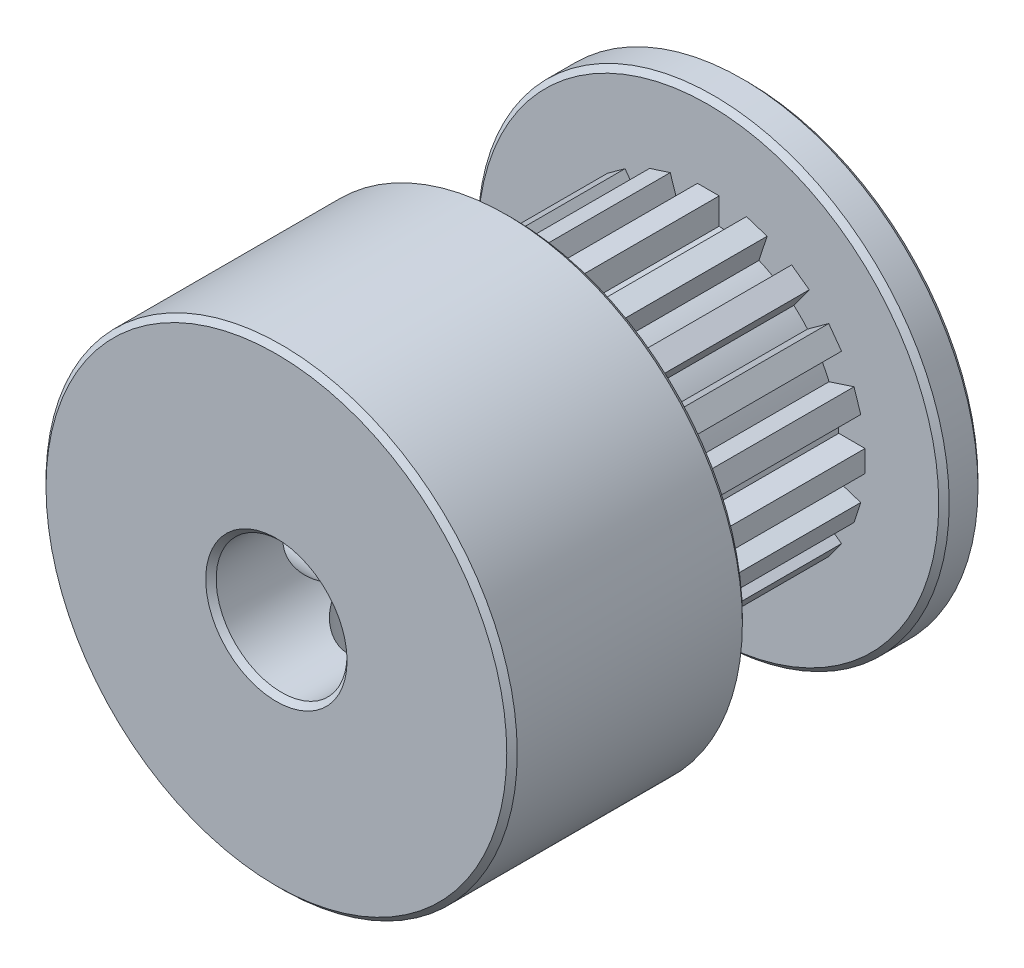
SolidWorks part; units mm, degrees
ref_plane "前视基准面" through (0, 0, 0) normal (0, 0, 1) x (1, 0, 0)
ref_plane "上视基准面" through (0, 0, 0) normal (0, 1, 0) x (1, 0, 0)
ref_plane "右视基准面" through (0, 0, 0) normal (1, 0, 0) x (0, 0, -1)
sketch "草图1" plane through (0, 0, 0) normal (0, 0, 1) x (1, 0, 0)
  circle A0 centre (0, 0) radius 2.5
  circle A1 centre (0, 0) radius 9
  dimension "D1" = 5
  dimension "D2" = 18
extrude "凸台-拉伸1" add sketch "草图1" along normal blind 1.5
sketch "草图2" plane through (0, 0, 1.5) normal (0, 0, 1) x (1, 0, 0)
  line L0 (0, 6) -> (0, 0) construction
  line L1 (-0.415, 5.9856) -> (-0.415, 4.9827)
  line L2 (-0.415, 5.9856) -> (0.415, 5.9856)
  line L3 (0.415, 5.9856) -> (0.415, 4.9827)
  line L4 (1.455, 5.8209) -> (1.1451, 4.8671)
  line L5 (2.2444, 5.5644) -> (1.9344, 4.6106)
  line L6 (1.455, 5.8209) -> (2.2444, 5.5644)
  line L7 (3.1825, 5.0864) -> (2.593, 4.2751)
  line L8 (3.854, 4.5985) -> (3.2645, 3.7872)
  line L9 (3.1825, 5.0864) -> (3.854, 4.5985)
  line L10 (4.5985, 3.854) -> (3.7872, 3.2645)
  line L11 (5.0864, 3.1825) -> (4.2751, 2.593)
  line L12 (4.5985, 3.854) -> (5.0864, 3.1825)
  line L13 (5.5644, 2.2444) -> (4.6106, 1.9344)
  line L14 (5.8209, 1.455) -> (4.8671, 1.1451)
  line L15 (5.5644, 2.2444) -> (5.8209, 1.455)
  line L16 (5.9856, 0.415) -> (4.9827, 0.415)
  line L17 (5.9856, -0.415) -> (4.9827, -0.415)
  line L18 (5.9856, 0.415) -> (5.9856, -0.415)
  line L19 (5.8209, -1.455) -> (4.8671, -1.1451)
  line L20 (5.5644, -2.2444) -> (4.6106, -1.9344)
  line L21 (5.8209, -1.455) -> (5.5644, -2.2444)
  line L22 (5.0864, -3.1825) -> (4.2751, -2.593)
  line L23 (4.5985, -3.854) -> (3.7872, -3.2645)
  line L24 (5.0864, -3.1825) -> (4.5985, -3.854)
  line L25 (3.854, -4.5985) -> (3.2645, -3.7872)
  line L26 (3.1825, -5.0864) -> (2.593, -4.2751)
  line L27 (3.854, -4.5985) -> (3.1825, -5.0864)
  line L28 (2.2444, -5.5644) -> (1.9344, -4.6106)
  line L29 (1.455, -5.8209) -> (1.1451, -4.8671)
  line L30 (2.2444, -5.5644) -> (1.455, -5.8209)
  line L31 (0.415, -5.9856) -> (0.415, -4.9827)
  line L32 (-0.415, -5.9856) -> (-0.415, -4.9827)
  line L33 (0.415, -5.9856) -> (-0.415, -5.9856)
  line L34 (-1.455, -5.8209) -> (-1.1451, -4.8671)
  line L35 (-2.2444, -5.5644) -> (-1.9344, -4.6106)
  line L36 (-1.455, -5.8209) -> (-2.2444, -5.5644)
  line L37 (-3.1825, -5.0864) -> (-2.593, -4.2751)
  line L38 (-3.854, -4.5985) -> (-3.2645, -3.7872)
  line L39 (-3.1825, -5.0864) -> (-3.854, -4.5985)
  line L40 (-4.5985, -3.854) -> (-3.7872, -3.2645)
  line L41 (-5.0864, -3.1825) -> (-4.2751, -2.593)
  line L42 (-4.5985, -3.854) -> (-5.0864, -3.1825)
  line L43 (-5.5644, -2.2444) -> (-4.6106, -1.9344)
  line L44 (-5.8209, -1.455) -> (-4.8671, -1.1451)
  line L45 (-5.5644, -2.2444) -> (-5.8209, -1.455)
  line L46 (-5.9856, -0.415) -> (-4.9827, -0.415)
  line L47 (-5.9856, 0.415) -> (-4.9827, 0.415)
  line L48 (-5.9856, -0.415) -> (-5.9856, 0.415)
  line L49 (-5.8209, 1.455) -> (-4.8671, 1.1451)
  line L50 (-5.5644, 2.2444) -> (-4.6106, 1.9344)
  line L51 (-5.8209, 1.455) -> (-5.5644, 2.2444)
  line L52 (-5.0864, 3.1825) -> (-4.2751, 2.593)
  line L53 (-4.5985, 3.854) -> (-3.7872, 3.2645)
  line L54 (-5.0864, 3.1825) -> (-4.5985, 3.854)
  line L55 (-3.854, 4.5985) -> (-3.2645, 3.7872)
  line L56 (-3.1825, 5.0864) -> (-2.593, 4.2751)
  line L57 (-3.854, 4.5985) -> (-3.1825, 5.0864)
  line L58 (-2.2444, 5.5644) -> (-1.9344, 4.6106)
  line L59 (-1.455, 5.8209) -> (-1.1451, 4.8671)
  line L60 (-2.2444, 5.5644) -> (-1.455, 5.8209)
  circle A0 centre (0, 0) radius 6 construction
  circle A1 centre (0, 0) radius 2.5 construction
  circle A2 centre (0, 0) radius 2.5
  arc A3 (-1.9344, 4.6106) -> (-2.593, 4.2751) centre (0, 0) ccw
  arc A4 (-0.415, 4.9827) -> (-1.1451, 4.8671) centre (0, 0) ccw
  arc A5 (1.1451, 4.8671) -> (0.415, 4.9827) centre (0, 0) ccw
  arc A6 (2.593, 4.2751) -> (1.9344, 4.6106) centre (0, 0) ccw
  arc A7 (3.7872, 3.2645) -> (3.2645, 3.7872) centre (0, 0) ccw
  arc A8 (4.6106, 1.9344) -> (4.2751, 2.593) centre (0, 0) ccw
  arc A9 (4.9827, 0.415) -> (4.8671, 1.1451) centre (0, 0) ccw
  arc A10 (4.8671, -1.1451) -> (4.9827, -0.415) centre (0, 0) ccw
  arc A11 (4.2751, -2.593) -> (4.6106, -1.9344) centre (0, 0) ccw
  arc A12 (3.2645, -3.7872) -> (3.7872, -3.2645) centre (0, 0) ccw
  arc A13 (0.415, -4.9827) -> (1.1451, -4.8671) centre (0, 0) ccw
  arc A14 (-2.593, -4.2751) -> (-1.9344, -4.6106) centre (0, 0) ccw
  arc A15 (-3.7872, -3.2645) -> (-3.2645, -3.7872) centre (0, 0) ccw
  arc A16 (-1.1451, -4.8671) -> (-0.415, -4.9827) centre (0, 0) ccw
  arc A17 (1.9344, -4.6106) -> (2.593, -4.2751) centre (0, 0) ccw
  arc A18 (-4.6106, -1.9344) -> (-4.2751, -2.593) centre (0, 0) ccw
  arc A19 (-4.9827, -0.415) -> (-4.8671, -1.1451) centre (0, 0) ccw
  arc A20 (-4.8671, 1.1451) -> (-4.9827, 0.415) centre (0, 0) ccw
  arc A21 (-4.2751, 2.593) -> (-4.6106, 1.9344) centre (0, 0) ccw
  arc A22 (-3.2645, 3.7872) -> (-3.7872, 3.2645) centre (0, 0) ccw
  point P89 (0, 0)
  dimension "D1" = 12
  dimension "D2" = 10
  dimension "D3" = 0.83
  dimension "D4" = 20
extrude "凸台-拉伸2" add sketch "草图2" along normal blind 7.5
sketch "草图3" plane through (0, 0, 9) normal (0, 0, 1) x (1, 0, 0)
  circle A0 centre (0, 0) radius 2.5 construction
  circle A1 centre (0, 0) radius 9
  circle A2 centre (0, 0) radius 9
  circle A3 centre (0, 0) radius 2.5
  dimension "D1" = 0
extrude "凸台-拉伸3" add sketch "草图3" along normal blind 9
chamfer "倒角2" distance 0.2 angle 45 6 edges at (2.5, 0, 18) (9, 0, 18) (2.5, 0, 0) (9, 0, 9) (9, 0, 1.5) (9, 0, 0)
sketch "草图4" plane through (0, 0, 0) normal (0, 1, 0) x (1, 0, 0)
  line L0 (9, -1.3) -> (9, -0.2) construction
  line L1 (-8.8, -18) -> (8.8, -18) construction
  circle A0 centre (0, -13.5) radius 1.75
  dimension "D1" = 3.5
  dimension "D3" = 4.5
  dimension "D2" = 9
extrude "切除-拉伸1" cut sketch "草图4" against normal blind 10 contours A0
sketch "草图5" plane through (0, 0, 0) normal (1, 0, 0) x (0, 0, -1)
  line L0 (-18, 8.8) -> (-18, -8.8) construction
  line L1 (-1.3, -9) -> (-0.2, -9) construction
  circle A0 centre (-13.5, 0) radius 1.75
  dimension "D1" = 3.5
  dimension "D2" = 4.5
  dimension "D3" = 9
extrude "切除-拉伸2" cut sketch "草图5" against normal blind 10
